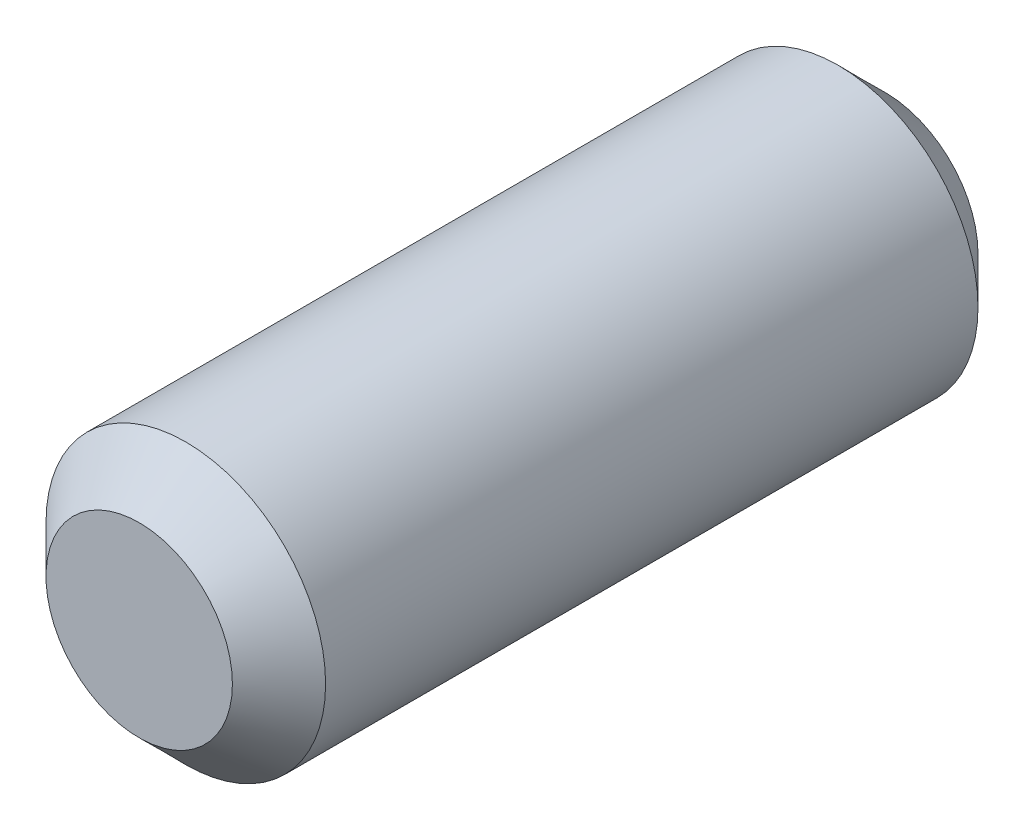
SolidWorks part; units mm, degrees
material "AISI 304"
ref_plane "前视基准面" through (0, 0, 0) normal (0, 0, 1) x (1, 0, 0)
ref_plane "上视基准面" through (0, 0, 0) normal (0, 1, 0) x (1, 0, 0)
ref_plane "右视基准面" through (0, 0, 0) normal (1, 0, 0) x (0, 0, -1)
other "Configuration Table"
sketch "草图1" plane through (0, 0, 0) normal (0, 0, 1) x (1, 0, 0)
  circle A0 centre (0, 0) radius 1.5
  dimension "D1" = 3
extrude "凸台-拉伸1" add sketch "草图1" along normal blind 8
chamfer "倒角1" distance 0.5 angle 45 2 edges at (1.5, 0, 0) (1.5, 0, 8)
